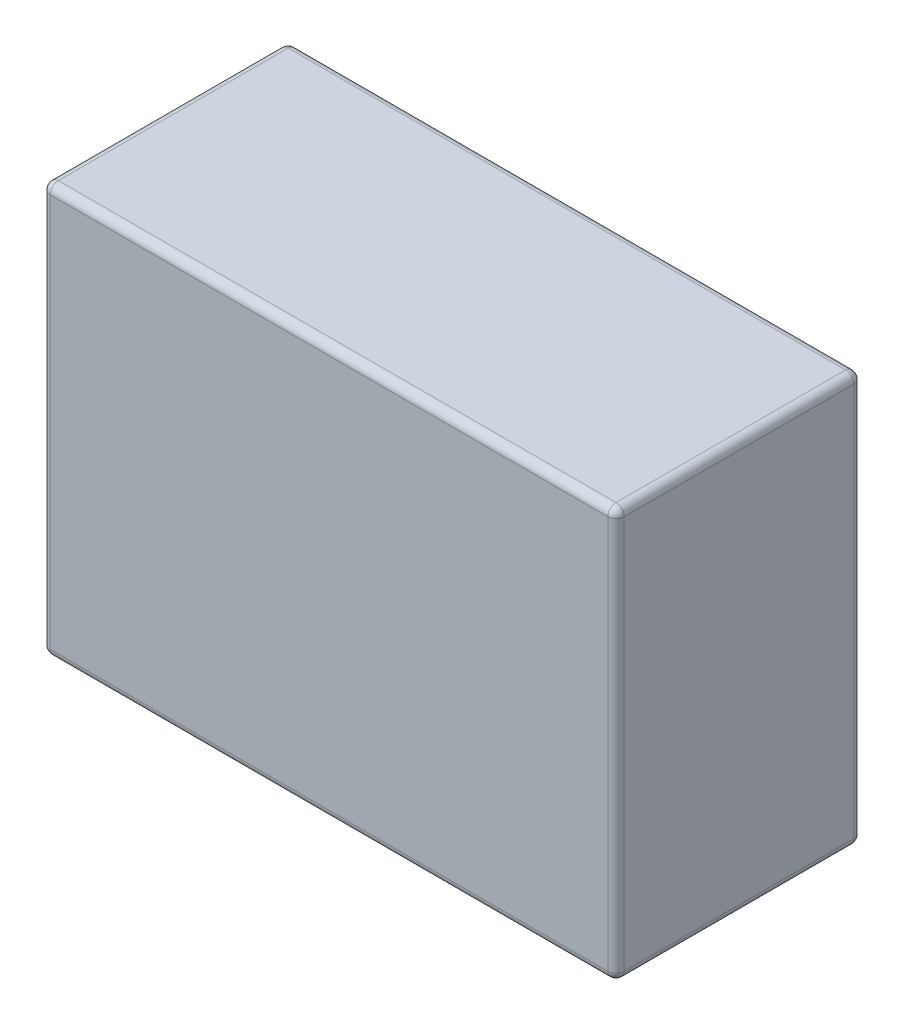
SolidWorks part; units mm, degrees
ref_plane "前视基准面" through (0, 0, 0) normal (0, 0, 1) x (1, 0, 0)
ref_plane "上视基准面" through (0, 0, 0) normal (0, 1, 0) x (1, 0, 0)
ref_plane "右视基准面" through (0, 0, 0) normal (1, 0, 0) x (0, 0, -1)
sketch "草图1" plane through (0, 0, 0) normal (0, 1, 0) x (1, 0, 0)
  line L1 (350, -150) -> (-350, -150)
  line L2 (350, -150) -> (350, 150)
  line L3 (350, 150) -> (-350, 150)
  line L4 (-350, -150) -> (-350, 150)
  line L5 (350, -150) -> (-350, 150) construction
  line L6 (350, 150) -> (-350, -150) construction
  point P0 (0, 0)
  dimension "D1" = 300
  dimension "D2" = 700
extrude "凸台-拉伸1" add sketch "草图1" along normal blind 500
fillet "圆角1" radius 10 12 edges at (350, 0, 0) (350, 250, 150) (0, 0, 150) (-350, 250, 150) (-350, 0, 0) (350, 250, -150) (-350, 250, -150) (0, 0, -150) (0, 500, -150) (350, 500, 0) (0, 500, 150) (-350, 500, 0)
sketch "草图2" plane through (0, 0, -150) normal (0, 0, -1) x (-1, 0, 0)
  line L1 (-322.5903, 467.8485) -> (328.4093, 467.8485)
  line L2 (-322.5903, 467.8485) -> (-322.5903, 361.6519)
  line L3 (-322.5903, 361.6519) -> (328.4093, 361.6519)
  line L4 (328.4093, 467.8485) -> (328.4093, 361.6519)
  line L5 (-322.5903, 250.3637) -> (328.4093, 250.3637)
  line L6 (-322.5903, 250.3637) -> (-322.5903, 120.1638)
  line L7 (-322.5903, 120.1638) -> (328.4093, 120.1638)
  line L8 (328.4093, 250.3637) -> (328.4093, 120.1638)
extrude "切除-拉伸1" cut sketch "草图2" against normal blind 280
